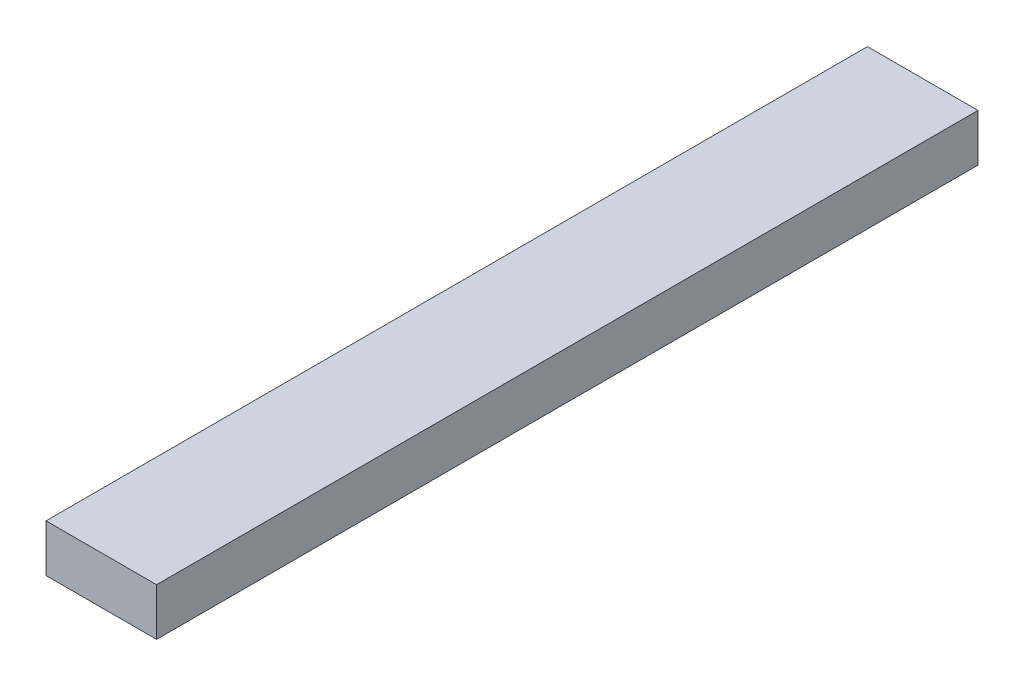
SolidWorks part; units mm, degrees
material "Pine"
ref_plane "Front Plane" through (0, 0, 0) normal (0, 0, 1) x (1, 0, 0)
ref_plane "Top Plane" through (0, 0, 0) normal (0, 1, 0) x (1, 0, 0)
ref_plane "Right Plane" through (0, 0, 0) normal (1, 0, 0) x (0, 0, -1)
sketch "Sketch1" plane through (0, 0, 0) normal (0, 0, 1) x (1, 0, 0)
  line L1 (0, 0) -> (88.9, 0)
  line L2 (0, 0) -> (0, 38.1)
  line L3 (0, 38.1) -> (88.9, 38.1)
  line L4 (88.9, 0) -> (88.9, 38.1)
  dimension "D1" = 88.9
  dimension "D2" = 38.1
extrude "Boss-Extrude1" add sketch "Sketch1" along normal blind 660.4
sketch "Sketch2" plane through (0, 0, 0) normal (0, 0, -1) x (-1, 0, 0)
  line L1 (-88.9, 0) -> (-88.9, 38.1) construction
  line L2 (0, 38.1) -> (0, 0) construction
  line L3 (-44.45, 19.05) -> (-88.9, 19.05) construction
  line L4 (-44.45, 19.05) -> (0, 19.05) construction
  circle A0 centre (-66.675, 19.05) radius 0.8763
  circle A1 centre (-22.225, 19.05) radius 0.8763
  dimension "D1" = 1.7526
sketch "Sketch3" plane through (0, 0, 0) normal (0, -1, 0) x (1, 0, 0)
  line L0 (44.45, 660.4) -> (44.45, 615.95) construction
  line L1 (0, 660.4) -> (88.9, 660.4) construction
  line L2 (44.45, 615.95) -> (44.45, 571.5) construction
  line L3 (88.9, 330.2) -> (0, 330.2) construction
  line L4 (88.9, 660.4) -> (88.9, 0) construction
  line L5 (0, 660.4) -> (0, 0) construction
  line L6 (44.45, 330.2) -> (44.45, 374.65) construction
  line L7 (44.45, 330.2) -> (44.45, 285.75) construction
  circle A0 centre (44.45, 638.175) radius 0.8763
  circle A1 centre (44.45, 593.725) radius 0.8763
  circle A2 centre (44.45, 22.225) radius 0.8763
  circle A3 centre (44.45, 66.675) radius 0.8763
  circle A4 centre (44.45, 307.975) radius 0.8763
  circle A5 centre (44.45, 352.425) radius 0.8763
  dimension "D2" = 1.7526
  dimension "D4" = 1.7526
  dimension "D1" = 88.9
  dimension "D3" = 88.9
equation "\"length\"= 20"
equation "\"D1@Boss-Extrude1\" = \"length\""
equation "\"length\"= 22"
equation "\"length\"= 36"
equation "\"length\"= 26"
equation "\"length\"= 27"
equation "\"length\"= 28"
equation "\"length\"= 39"
equation "\"length\"= 48"
equation "\"length\"= 30"
equation "\"length\"= 32"
